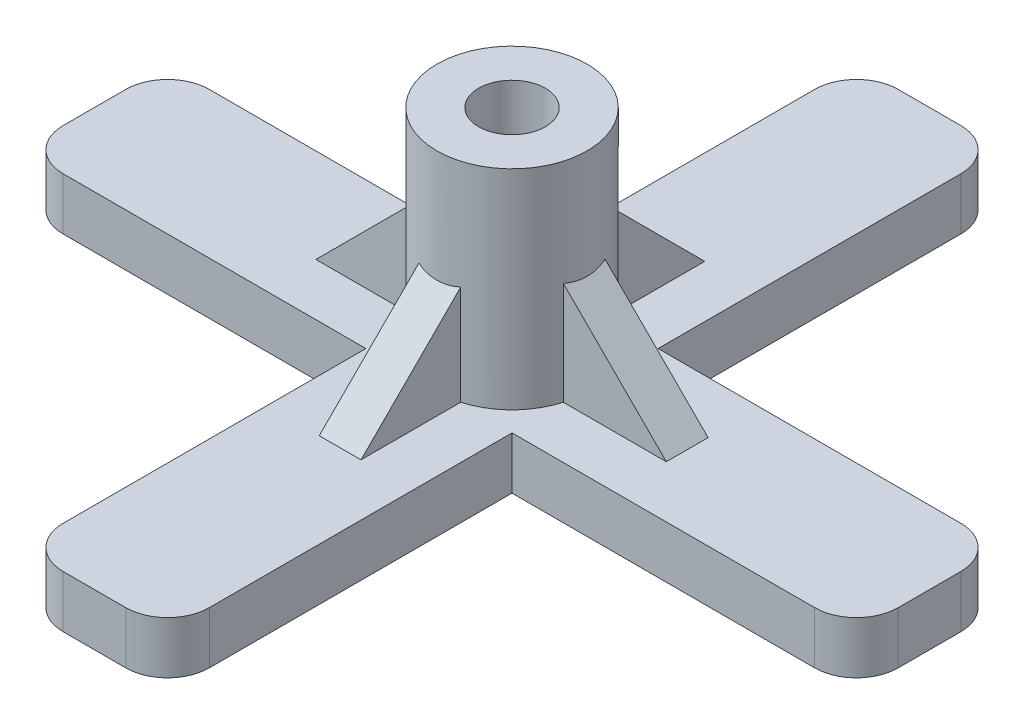
SolidWorks part; units mm, degrees
ref_plane "Front Plane" through (0, 0, 0) normal (0, 0, 1) x (1, 0, 0)
ref_plane "Top Plane" through (0, 0, 0) normal (0, 1, 0) x (1, 0, 0)
ref_plane "Right Plane" through (0, 0, 0) normal (1, 0, 0) x (0, 0, -1)
sketch "Sketch1" plane through (0, 0, 0) normal (0, 1, 0) x (1, 0, 0)
  line L0 (-25.4, 1.905) -> (-25.4, -1.905)
  line L1 (-1.905, -25.4) -> (1.905, -25.4)
  line L2 (-4.445, -22.86) -> (-4.445, -4.445)
  line L4 (4.445, -22.86) -> (4.445, -4.445)
  line L5 (-22.86, 4.445) -> (-4.445, 4.445)
  line L7 (-22.86, -4.445) -> (-4.445, -4.445)
  line L8 (1.905, 25.4) -> (-1.905, 25.4)
  line L9 (4.445, 22.86) -> (4.445, 4.445)
  line L11 (-4.445, 22.86) -> (-4.445, 4.445)
  line L12 (25.4, -1.905) -> (25.4, 1.905)
  line L13 (22.86, -4.445) -> (4.445, -4.445)
  line L15 (22.86, 4.445) -> (4.445, 4.445)
  arc A0 (1.905, 25.4) -> (4.445, 22.86) centre (1.905, 22.86) cw
  arc A1 (-1.905, 25.4) -> (-4.445, 22.86) centre (-1.905, 22.86) ccw
  arc A2 (-25.4, 1.905) -> (-22.86, 4.445) centre (-22.86, 1.905) cw
  arc A3 (-25.4, -1.905) -> (-22.86, -4.445) centre (-22.86, -1.905) ccw
  arc A4 (-1.905, -25.4) -> (-4.445, -22.86) centre (-1.905, -22.86) cw
  arc A5 (1.905, -25.4) -> (4.445, -22.86) centre (1.905, -22.86) ccw
  arc A6 (25.4, -1.905) -> (22.86, -4.445) centre (22.86, -1.905) cw
  arc A7 (25.4, 1.905) -> (22.86, 4.445) centre (22.86, 1.905) ccw
  point P21 (0, 0)
  dimension "D3" = 2.54
  dimension "D1" = 8.89
  dimension "D2" = 4
extrude "Boss-Extrude1" add sketch "Sketch1" along normal blind 3.175
sketch "Sketch2" plane through (0, 3.175, 0) normal (0, 1, 0) x (1, 0, 0)
  circle A0 centre (0, 0) radius 2.032
  circle A1 centre (0, 0) radius 4.572
  dimension "D1" = 4.064
  dimension "D2" = 2.54
extrude "Boss-Extrude2" add sketch "Sketch2" along normal blind 12.7
sketch "Sketch9" plane through (0, 0, 0) normal (0, 0, 1) x (1, 0, 0)
  line L0 (-10.6593, 3.175) -> (-4.3093, 3.175)
  line L1 (-22.86, 3.175) -> (-4.445, 3.175) construction
  line L2 (-4.3093, 3.175) -> (-4.3093, 9.525)
  line L3 (-4.3093, 9.525) -> (-10.6593, 3.175)
  line L4 (0, 0) -> (0, 25.1709) construction
  line L5 (10.6593, 3.175) -> (4.3093, 3.175)
  line L6 (4.3093, 3.175) -> (4.3093, 9.525)
  line L7 (4.3093, 9.525) -> (10.6593, 3.175)
  line L8 (-1.905, 3.175) -> (-4.445, 3.175) construction
  point P12 (0, 0)
  point P13 (-4.572, 9.525)
  point P14 (0, 0)
  point P15 (-4.572, 9.525)
  point P16 (-4.572, 3.175)
  point P17 (0, 0)
  point P18 (-4.3361, 3.175)
  point P21 (-4.3093, 9.525)
  dimension "D1" = 6.35
  dimension "D2" = 6.35
extrude "Boss-Extrude3" add sketch "Sketch9" along normal mid plane 2.54
sketch "Sketch10" plane through (0, 0, 0) normal (1, 0, 0) x (0, 0, -1)
  line L0 (-10.4566, 3.175) -> (-4.1066, 3.175)
  line L1 (-22.86, 3.175) -> (-4.445, 3.175) construction
  line L2 (-1.905, 3.175) -> (-4.445, 3.175) construction
  line L3 (-4.1066, 3.175) -> (-4.1066, 9.525)
  line L4 (-4.1066, 9.525) -> (-10.4566, 3.175)
  line L5 (0, 0) -> (0, 28.1157) construction
  line L6 (0, 28.1157) -> (-20.844, 18.1547) construction
  line L7 (-20.844, 18.1547) -> (-20.3076, 18.411) construction
  line L8 (-20.3076, 18.411) -> (-20.3076, 18.2828) construction
  line L9 (4.1066, 9.525) -> (10.4566, 3.175)
  line L10 (4.1066, 3.175) -> (4.1066, 9.525)
  line L11 (10.4566, 3.175) -> (4.1066, 3.175)
  point P0 (-11.5273, 3.175)
  point P12 (-11.4954, 3.175)
  point P15 (-10.0751, 3.175)
  point P16 (0, 0)
  point P17 (0, 0)
  point P18 (0, 0)
  point P19 (0, 0)
  dimension "D1" = 6.35
  dimension "D2" = 6.35
extrude "Boss-Extrude4" add sketch "Sketch10" along normal mid plane 2.54
